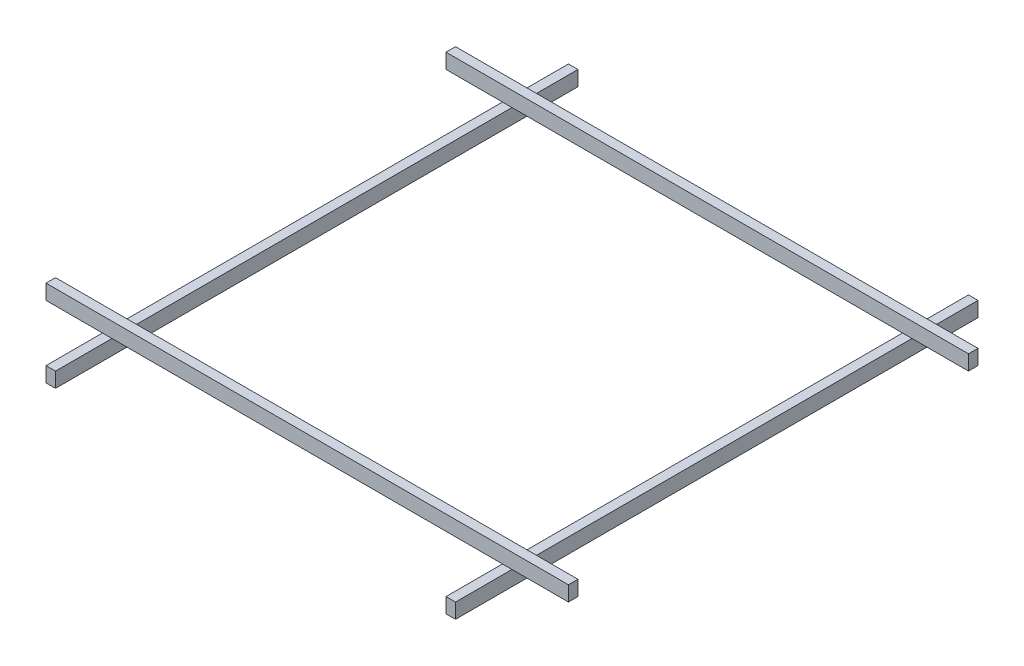
SolidWorks part; units mm, degrees
material "Doug Fir"
ref_plane "Front Plane" through (0, 0, 0) normal (0, 0, 1) x (1, 0, 0)
ref_plane "Top Plane" through (0, 0, 0) normal (0, 1, 0) x (1, 0, 0)
ref_plane "Right Plane" through (0, 0, 0) normal (1, 0, 0) x (0, 0, -1)
sketch "Lower Level" plane through (0, 0, 0) normal (0, 1, 0) x (1, 0, 0)
  line L0 (266.7, 0) -> (266.7, 4876.8)
  line L1 (4000.5, 0) -> (4000.5, 4876.8)
  line L2 (266.7, 2438.4) -> (4000.5, 2438.4) construction
  point P7 (2133.6, 2438.4)
  dimension "D1" = 4876.8
  dimension "D2" = 1866.9
ref_plane "Plane2" through (0, 139.7, 0) normal (0, 1, 0) x (1, 0, 0)
sketch "Sketch12" plane through (0, 139.7, 0) normal (0, 1, 0) x (1, 0, 0)
  line L0 (-304.8, 4305.3) -> (4572, 4305.3)
  line L1 (4572, 571.5) -> (-304.8, 571.5)
  line L2 (2133.6, 4305.3) -> (2133.6, 571.5) construction
  point P0 (2133.6, 2438.4)
  point P6 (2133.6, 571.5)
  point P7 (2133.6, 4305.3)
  point P10 (2133.6, 2438.4)
  dimension "D1" = 4876.8
  dimension "D2" = 1866.9
other "Profiles 4X6(1)"
ref_plane "Plane1" through (266.7, 0, 0) normal (0, 0, -1) x (-1, 0, 0)
sketch "Sketch1" plane through (266.7, 0, 0) normal (0, 0, -1) x (-1, 0, 0)
  line L1 (-44.45, 69.85) -> (44.45, 69.85)
  line L2 (-44.45, 69.85) -> (-44.45, -69.85)
  line L3 (-44.45, -69.85) -> (44.45, -69.85)
  line L4 (44.45, 69.85) -> (44.45, -69.85)
  line L5 (-44.45, 69.85) -> (44.45, -69.85) construction
  line L6 (-44.45, -69.85) -> (44.45, 69.85) construction
  point P0 (0, 0)
  point P6 (0, 69.85)
  point P7 (0, -69.85)
  point P8 (44.45, 0)
  point P9 (-44.45, 0)
  point P10 (0, 0)
  dimension "D1" = 88.9
  dimension "D2" = 139.7
sketch3d "3DSketch2"
  line L0 (2133.6, 139.7, -2438.4) -> (2133.6, 0, -2438.4)
  line L1 (266.7, 0, -2438.4) -> (4000.5, 0, -2438.4) construction
equation "\"Width\" = 73.5"
equation "\"Length\"=192"
equation "\"D1@Lower Level\"=\"Length\""
equation "\"D2@Lower Level\"=\"Width\""
equation "\"D1@Sketch12\"=\"Length\""
equation "\"D2@Sketch12\"=\"Width\""
